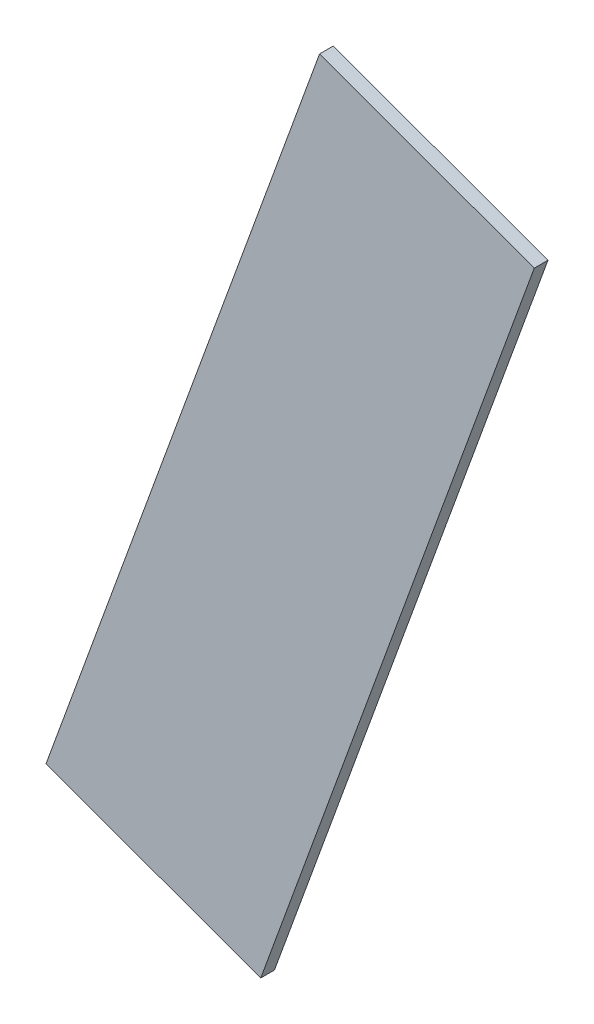
SolidWorks part; units mm, degrees
material "Thornel Mat VMA"
ref_plane "前视基准面" through (0, 0, 0) normal (0, 0, 1) x (1, 0, 0)
ref_plane "上视基准面" through (0, 0, 0) normal (0, 1, 0) x (1, 0, 0)
ref_plane "右视基准面" through (0, 0, 0) normal (1, 0, 0) x (0, 0, -1)
other "Configuration Table"
sketch "草图1" plane through (0, 0, 0) normal (0, 0, 1) x (1, 0, 0)
  line L0 (366.8083, 667.0656) -> (426.6619, 831.5118)
  line L3 (366.8083, 667.0656) -> (319.8237, 684.1666)
  line L4 (319.8237, 684.1666) -> (379.6772, 848.6128)
  line L7 (426.6619, 831.5118) -> (379.6772, 848.6128)
  line L9 (328.5815, 686.2999) -> (326.8714, 681.6014) construction
  dimension "D1" = 175
  dimension "D2" = 50
  dimension "D3" = 7.5
extrude "凸台-拉伸1" add sketch "草图1" along normal blind 3
